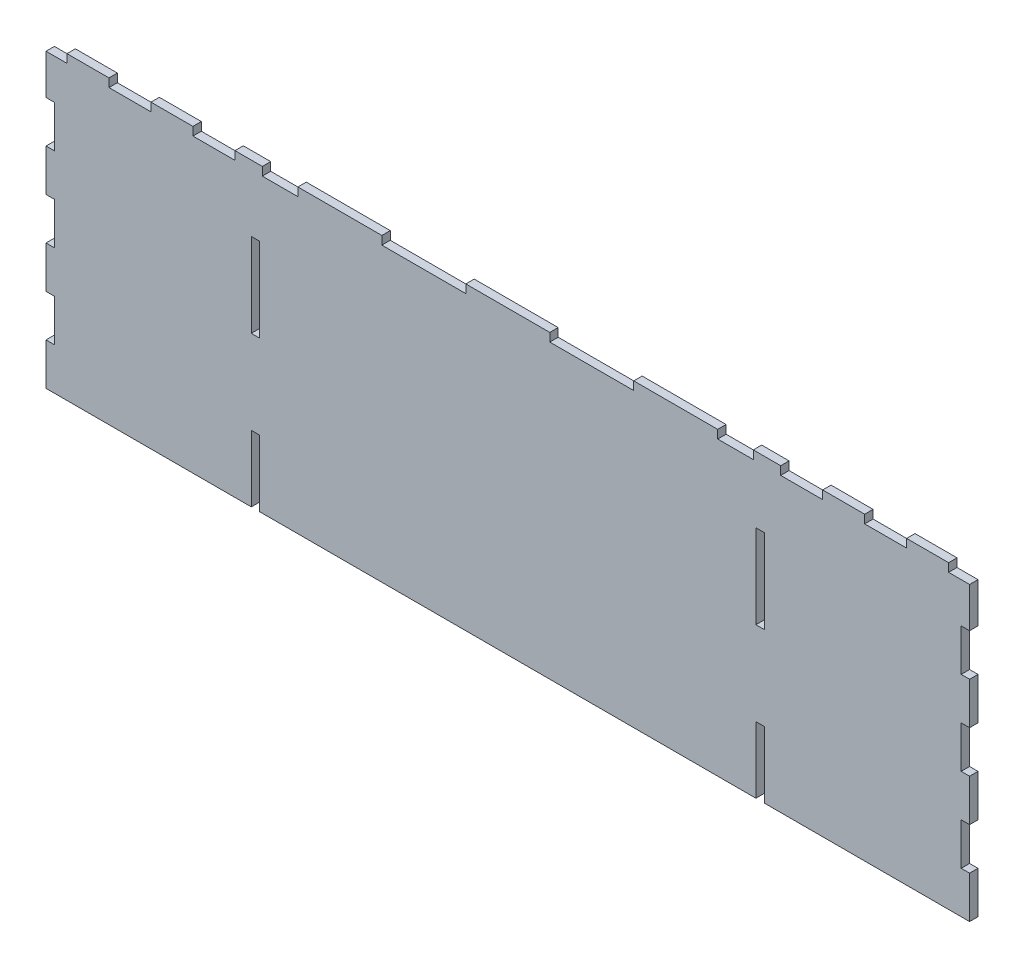
SolidWorks part; units mm, degrees
ref_plane "Front Plane" through (0, 0, 0) normal (0, 0, 1) x (1, 0, 0)
ref_plane "Top Plane" through (0, 0, 0) normal (0, 1, 0) x (1, 0, 0)
ref_plane "Right Plane" through (0, 0, 0) normal (1, 0, 0) x (0, 0, -1)
sketch "Sketch1" plane through (0, 0, 0) normal (0, 0, 1) x (1, 0, 0)
  line L1 (-139.7, 45.4343) -> (139.7, 45.4343)
  line L2 (-139.7, 45.4343) -> (-139.7, -45.4343)
  line L3 (-139.7, -45.4343) -> (139.7, -45.4343)
  line L4 (139.7, 45.4343) -> (139.7, -45.4343)
  line L5 (-139.7, 45.4343) -> (139.7, -45.4343) construction
  line L6 (-139.7, -45.4343) -> (139.7, 45.4343) construction
  point P0 (0, 0)
  dimension "D1" = 90.8685
  dimension "D2" = 279.4
extrude "Boss-Extrude1" add sketch "Sketch1" along normal blind 2.54
sketch "Sketch2" plane through (0, 0, 2.54) normal (0, 0, 1) x (1, 0, 0)
  line L0 (139.7, 45.4343) -> (-139.7, 45.4343) construction
  line L1 (146.05, 45.4343) -> (133.35, 45.4343)
  line L2 (146.05, 45.4343) -> (146.05, 42.8942)
  line L3 (146.05, 42.8942) -> (133.35, 42.8942)
  line L4 (133.35, 45.4343) -> (133.35, 42.8942)
  line L6 (139.7, -45.4343) -> (139.7, 45.4343) construction
  dimension "D1" = 6.35
  dimension "D2" = 12.7
  dimension "D3" = 2.54
extrude "Cut-Extrude1" cut sketch "Sketch2" against normal through all
pattern_linear "LPattern1" count 3 spacing 25.4 along (-1, 0, 0) of "Cut-Extrude1"
mirror "Mirror1" about plane through (0, 0, 0) normal (1, 0, 0) of "LPattern1", "Cut-Extrude1"
sketch "Sketch3" plane through (0, 0, 2.54) normal (0, 0, 1) x (1, 0, 0)
  line L0 (139.7, -45.4343) -> (139.7, 42.8942) construction
  line L1 (75.057, -25.3682) -> (77.597, -25.3683)
  line L2 (75.057, -25.3682) -> (75.057, -50.7683)
  line L3 (75.057, -50.7683) -> (77.597, -50.7683)
  line L4 (77.597, -25.3683) -> (77.597, -50.7683)
  line L5 (-139.7, -45.4343) -> (139.7, -45.4343) construction
  dimension "D1" = 25.4
  dimension "D2" = 2.54
  dimension "D3" = 62.103
  dimension "D4" = 20.066
extrude "Cut-Extrude2" cut sketch "Sketch3" against normal through all
pattern_linear "LPattern2" count 2 spacing 50.8 along (0, 1, 0) of "Cut-Extrude2"
mirror "Mirror2" about plane through (0, 0, 0) normal (1, 0, 0) of "LPattern2", "Cut-Extrude2"
sketch "Sketch4" plane through (0, 0, 2.54) normal (0, 0, 1) x (1, 0, 0)
  line L0 (139.7, -45.4343) -> (139.7, 42.8942) construction
  line L1 (139.7, -32.7343) -> (137.16, -32.7343)
  line L2 (139.7, -32.7343) -> (139.7, -20.0343)
  line L3 (139.7, -20.0343) -> (137.16, -20.0343)
  line L4 (137.16, -32.7343) -> (137.16, -20.0343)
  line L5 (77.597, -45.4343) -> (139.7, -45.4343) construction
  dimension "D1" = 12.7
  dimension "D2" = 12.7
  dimension "D3" = 2.54
extrude "Cut-Extrude3" cut sketch "Sketch4" against normal through all
pattern_linear "LPattern3" count 3 spacing 25.4 along (0, 1, 0) of "Cut-Extrude3"
mirror "Mirror3" about plane through (0, 0, 0) normal (1, 0, 0) of "LPattern3", "Cut-Extrude3"
sketch "Sketch5" plane through (0, 0, 2.54) normal (0, 0, 1) x (1, 0, 0)
  line L0 (82.55, 45.4343) -> (-82.55, 45.4343) construction
  line L1 (-38.1, 45.4343) -> (-12.7, 45.4343)
  line L2 (-38.1, 45.4343) -> (-38.1, 42.8942)
  line L3 (-38.1, 42.8942) -> (-12.7, 42.8942)
  line L4 (-12.7, 45.4343) -> (-12.7, 42.8942)
  line L6 (-63.5, 45.4343) -> (-74.2633, 45.4343)
  line L7 (-63.5, 45.4343) -> (-63.5, 42.8942)
  line L8 (-63.5, 42.8942) -> (-74.2633, 42.8942)
  line L9 (-74.2633, 45.4343) -> (-74.2633, 42.8942)
  dimension "D1" = 2.54
  dimension "D2" = 25.4
  dimension "D3" = 12.7
  dimension "D4" = 10.7633
  dimension "D5" = 25.4
extrude "Cut-Extrude4" cut sketch "Sketch5" against normal through all
mirror "Mirror4" about plane through (0, 0, 0) normal (1, 0, 0) of "Cut-Extrude4"
